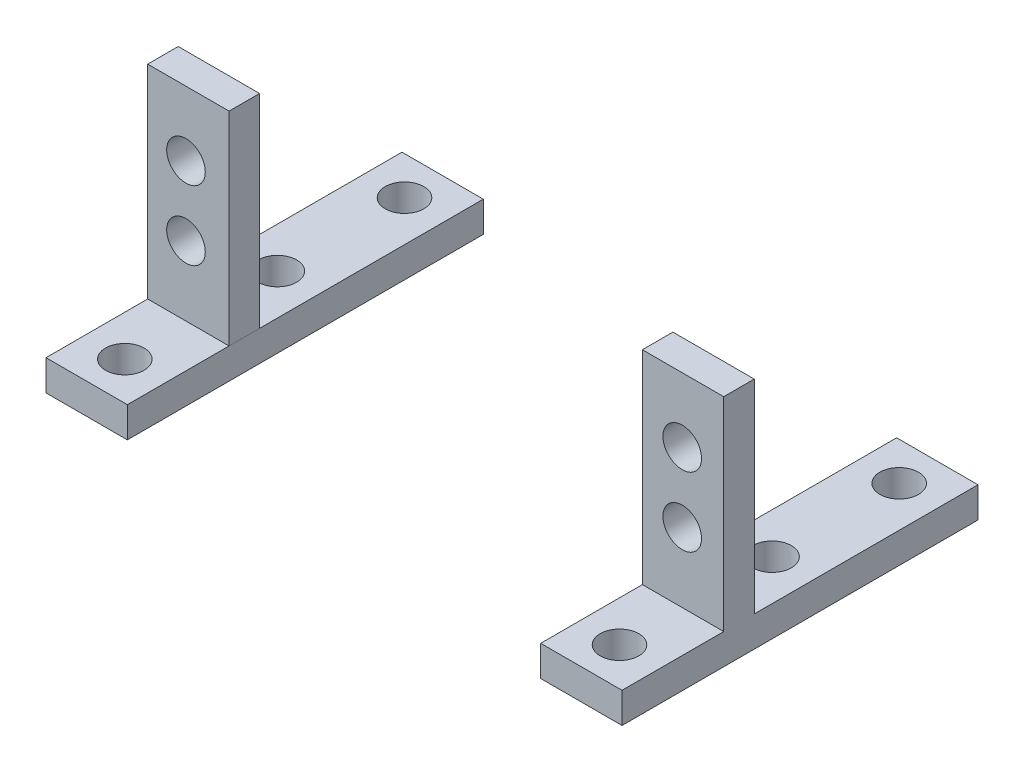
SolidWorks part; units mm, degrees
ref_plane "Front Plane" through (0, 0, 0) normal (0, 0, 1) x (1, 0, 0)
ref_plane "Top Plane" through (0, 0, 0) normal (0, 1, 0) x (1, 0, 0)
ref_plane "Right Plane" through (0, 0, 0) normal (1, 0, 0) x (0, 0, -1)
sketch "Sketch1" plane through (0, 0, 0) normal (0, 1, 0) x (1, 0, 0)
  line L1 (0, 35) -> (8, 35)
  line L2 (0, 35) -> (0, 0)
  line L3 (0, 0) -> (8, 0)
  line L4 (8, 35) -> (8, 0)
  line L5 (-48.64, 35) -> (-40.64, 35)
  line L6 (-48.64, 35) -> (-48.64, 0)
  line L7 (-48.64, 0) -> (-40.64, 0)
  line L8 (-40.64, 35) -> (-40.64, 0)
  dimension "D1" = 35
  dimension "D2" = 8
  dimension "D3" = 40.64
extrude "Boss-Extrude1" add sketch "Sketch1" along normal blind 3
sketch "Sketch2" plane through (0, 3, 0) normal (0, 1, 0) x (1, 0, 0)
  line L0 (0, 35) -> (0, 0) construction
  line L1 (0, 13) -> (8, 13)
  line L2 (0, 13) -> (0, 10)
  line L3 (0, 10) -> (8, 10)
  line L4 (8, 13) -> (8, 10)
  line L5 (8, 0) -> (8, 35) construction
  line L6 (0, 0) -> (8, 0) construction
  line L16 (-48.64, 35) -> (-48.64, 0) construction
  line L17 (-48.64, 13) -> (-40.64, 13)
  line L18 (-48.64, 13) -> (-48.64, 10)
  line L19 (-48.64, 10) -> (-40.64, 10)
  line L20 (-40.64, 13) -> (-40.64, 10)
  line L21 (-40.64, 0) -> (-40.64, 35) construction
  dimension "D1" = 3
  dimension "D2" = 10
extrude "Boss-Extrude2" add sketch "Sketch2" along normal blind 20
hole_wizard "#6 Clearance Hole1" positions "Sketch3" profile "Sketch4" hole size "#6" standard "ANSI Inch" end condition through all
sketch "Sketch3" plane through (0, 0, -10) normal (0, 0, 1) x (1, 0, 0)
  point P0 (-44.8768, 16.6416)
  point P2 (-44.8768, 9.8303)
  point P4 (3.9176, 16.6416)
  point P6 (3.9176, 9.8303)
  point P9 (0, 0)
  point P10 (0, 0)
  point P11 (0, 0)
  point P12 (0, 0)
  point P13 (0, 0)
sketch "Sketch4" plane through (-44.8768, 16.6416, -10) normal (1, 0, 0) x (0, -1, 0)
  line L0 (0, 0) -> (0, 25)
  line L1 (0, 25) -> (1.8986, 25)
  line L2 (1.8986, 25) -> (1.8986, 0)
  line L5 (1.8986, 0) -> (0, 0)
  line L11 (0, -6.35) -> (0, 107.95) construction
  dimension "Thru Hole Dia." = 3.7973
  dimension "Thru Hole Depth" = 25
hole_wizard "#6 Clearance Hole2" positions "Sketch5" profile "Sketch6" hole size "#6" standard "ANSI Inch" end condition through all
sketch "Sketch5" plane through (0, 3, 0) normal (0, 1, 0) x (1, 0, 0)
  line L0 (-48.64, 0) -> (-40.64, 0) construction
  line L1 (0, 0) -> (8, 0) construction
  point P0 (-44.64, 31.25)
  point P2 (-44.64, 18.75)
  point P4 (-44.64, 3.75)
  point P6 (4, 31.25)
  point P8 (4, 18.75)
  point P10 (4, 3.75)
  point P22 (-44.64, 0)
  point P26 (4, 0)
  dimension "D1" = 15
  dimension "D2" = 27.5
  dimension "D3" = 3.75
sketch "Sketch6" plane through (-44.64, 3, -31.25) normal (1, 0, 0) x (0, 0, 1)
  line L0 (0, 0) -> (0, 3)
  line L1 (0, 3) -> (1.8986, 3)
  line L2 (1.8986, 3) -> (1.8986, 0)
  line L5 (1.8986, 0) -> (0, 0)
  line L11 (0, -6.35) -> (0, 107.95) construction
  dimension "Thru Hole Dia." = 3.7973
  dimension "Thru Hole Depth" = 3
